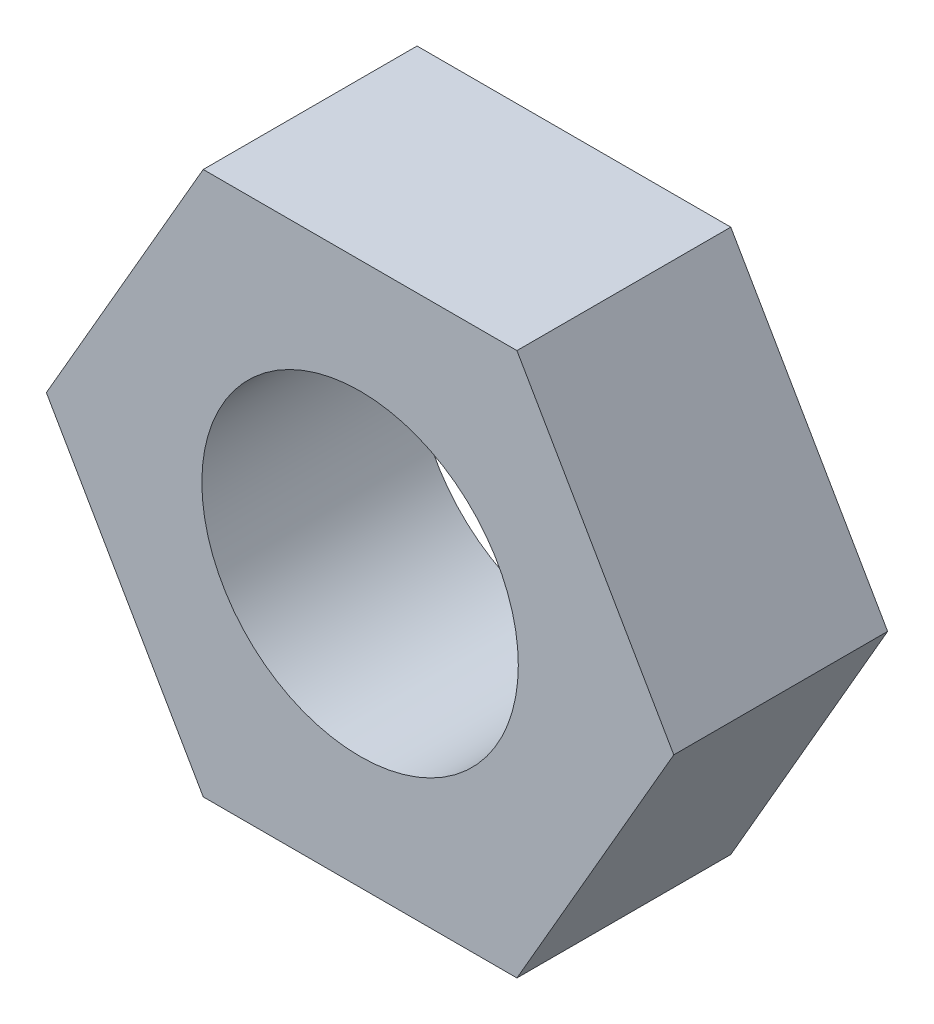
SolidWorks part; units mm, degrees
ref_plane "Front Plane" through (0, 0, 0) normal (0, 0, 1) x (1, 0, 0)
ref_plane "Top Plane" through (0, 0, 0) normal (0, 1, 0) x (1, 0, 0)
ref_plane "Right Plane" through (0, 0, 0) normal (1, 0, 0) x (0, 0, -1)
sketch "Sketch1" plane through (0, 0, 0) normal (0, 0, 1) x (1, 0, 0)
  line L1 (4.6578, 0) -> (2.3289, 4.0338)
  line L2 (2.3289, 4.0338) -> (-2.3289, 4.0338)
  line L3 (-2.3289, 4.0338) -> (-4.6578, 0)
  line L4 (-4.6578, 0) -> (-2.3289, -4.0338)
  line L5 (-2.3289, -4.0338) -> (2.3289, -4.0338)
  line L6 (2.3289, -4.0338) -> (4.6578, 0)
  circle A0 centre (0, 0) radius 4.0338 construction
  circle A1 centre (0, 0) radius 2.3495
  dimension "D1" = 4.699
extrude "Boss-Extrude1" add sketch "Sketch1" along normal blind 3.175
